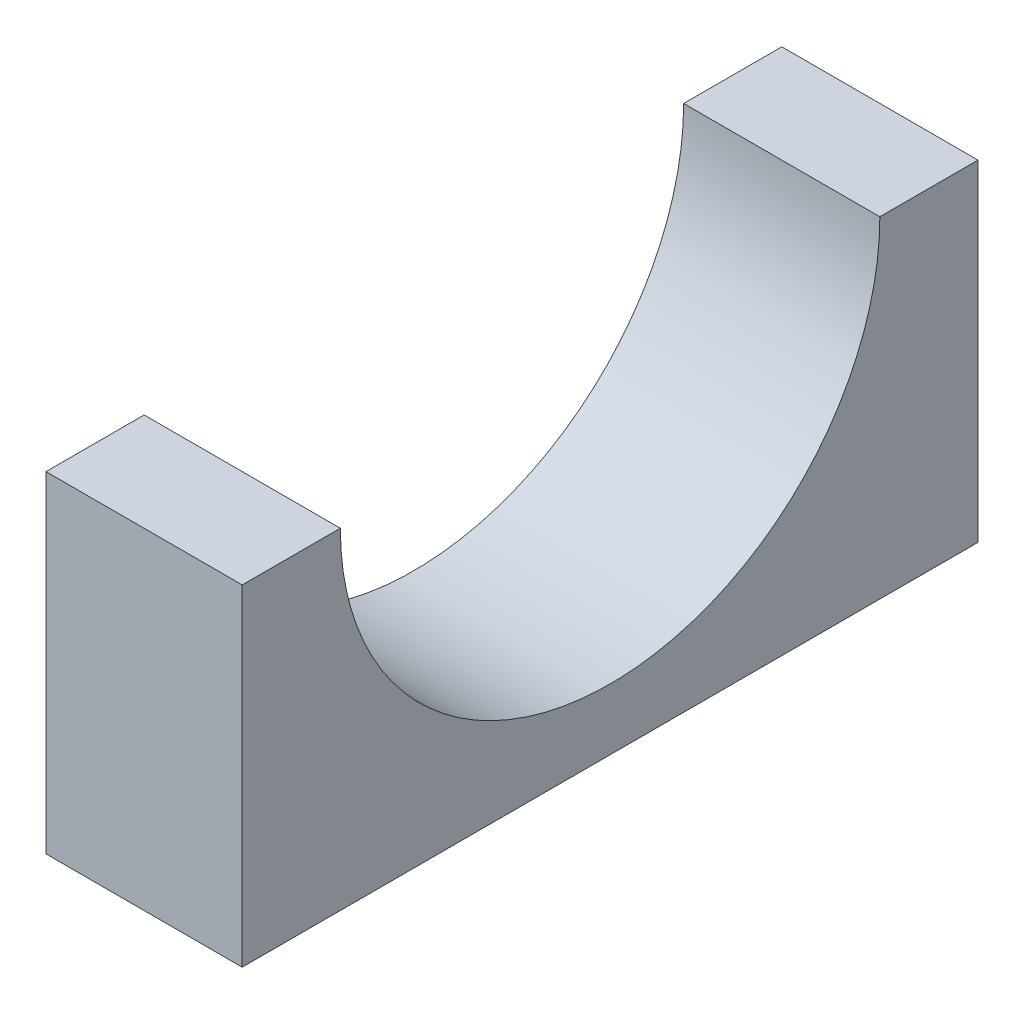
SolidWorks part; units mm, degrees
material "Aluminum"
ref_plane "Front Plane" through (0, 0, 0) normal (0, 0, 1) x (1, 0, 0)
ref_plane "Top Plane" through (0, 0, 0) normal (0, 1, 0) x (1, 0, 0)
ref_plane "Right Plane" through (0, 0, 0) normal (1, 0, 0) x (0, 0, -1)
sketch "Sketch1" plane through (0, 0, 0) normal (1, 0, 0) x (0, 0, -1)
  line L0 (-11.002, 0) -> (-15.002, 0)
  line L1 (-15.002, 0) -> (-15.002, -13.5)
  line L2 (-15.002, -13.5) -> (15.0018, -13.5)
  line L3 (15.0018, -13.5) -> (15.0018, 0)
  line L4 (15.0018, 0) -> (11.0018, 0)
  line L5 (-11.002, 0) -> (-11, 0)
  line L6 (11.0018, 0) -> (11, 0)
  arc A0 (-11, 0) -> (11, 0) centre (0, 0) ccw
  dimension "D1" = 22
  dimension "D3" = 4
  dimension "D4" = 4
extrude "Boss-Extrude1" add sketch "Sketch1" along normal blind 8
hole_wizard "Tap Drill for M2.5x0.45 Tap1" positions "Sketch3" profile "Sketch4" hole size "M2.5x0.45" standard "ANSI Metric"
sketch "Sketch3" plane through (0, -13.5, 0) normal (0, -1, 0) x (-1, 0, 0)
  line L0 (-8, -15.002) -> (0, -15.002) construction
  line L1 (-8, 15.0018) -> (0, 15.0018) construction
  point P0 (-4, -12.502)
  point P2 (-4, 12.5018)
  dimension "D1" = 2.5
  dimension "D2" = 2.5
sketch "Sketch4" plane through (4, -13.5, 12.502) normal (1, 0, 0) x (0, 0, -1)
  line L0 (0, 0) -> (0, 6.5)
  line L1 (0, 6.5) -> (1.25, 6.5)
  line L2 (1.25, 6.5) -> (1.25, 0)
  line L5 (1.25, 0) -> (0, 0)
  line L10 (0, 6.5) -> (-1.25, 6.5) construction
  line L11 (0, -6.35) -> (0, 107.95) construction
  dimension "Hole Dia." = 2.5
  dimension "Hole Depth" = 6.5
  dimension "Drill Angle" = 180
